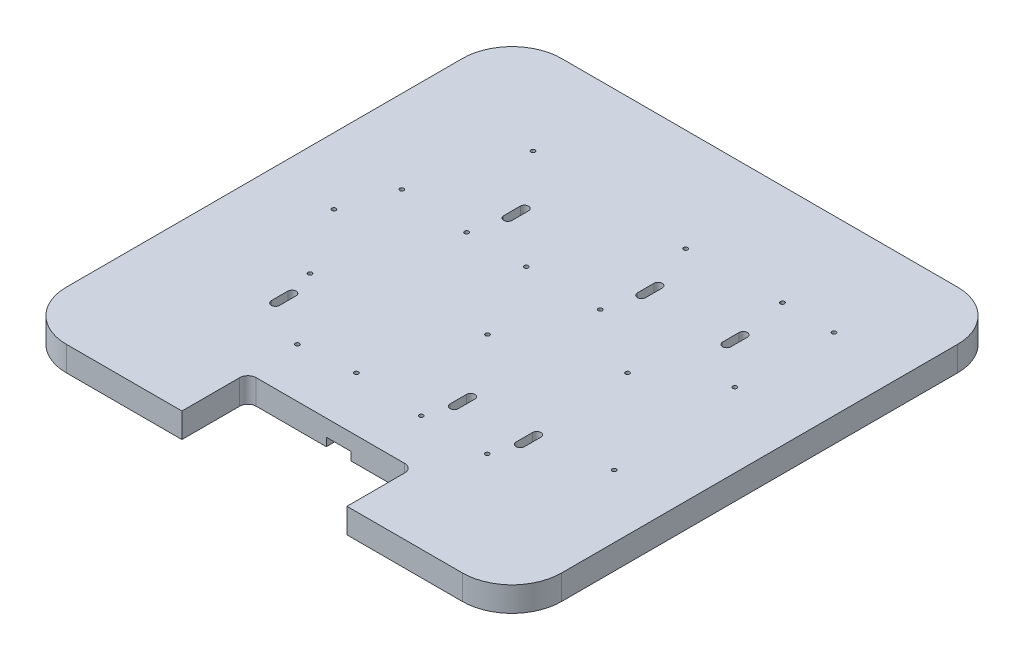
SolidWorks part; units mm, degrees
material "Красное дерево"
ref_plane "Спереди" through (0, 0, 0) normal (0, 0, 1) x (1, 0, 0)
ref_plane "Сверху" through (0, 0, 0) normal (0, 1, 0) x (1, 0, 0)
ref_plane "Справа" through (0, 0, 0) normal (1, 0, 0) x (0, 0, -1)
sketch "Эскиз основания" plane through (0, 0, 0) normal (0, 1, 0) x (1, 0, 0)
  line L0 (-90, -220) -> (90, -220)
  line L1 (-240, 300) -> (240, 300)
  line L2 (-300, 240) -> (-300, -240)
  line L3 (-240, -300) -> (-100, -300)
  line L4 (300, 240) -> (300, -240)
  line L5 (-100, -230) -> (-100, -300)
  line L7 (100, -230) -> (100, -300)
  line L8 (100, -300) -> (240, -300)
  arc A0 (240, -300) -> (300, -240) centre (240, -240) ccw
  arc A1 (240, 300) -> (300, 240) centre (240, 240) cw
  arc A2 (-240, 300) -> (-300, 240) centre (-240, 240) ccw
  arc A3 (-300, -240) -> (-240, -300) centre (-240, -240) ccw
  arc A6 (90, -220) -> (100, -230) centre (90, -230) cw
  arc A7 (-90, -220) -> (-100, -230) centre (-90, -230) ccw
  point P9 (300, 300)
  point P12 (-300, 300)
  point P15 (0, 0)
  dimension "D3" = 60
  dimension "D10" = 10
  dimension "D2" = 600
  dimension "D1" = 600
  dimension "D4" = 300
  dimension "D5" = 300
  dimension "D6" = 200
  dimension "D8" = 100
  dimension "D7" = 80
extrude "Основание" add sketch "Эскиз основания" against normal blind 30
sketch "Эскиз разметки под крепёж" plane through (0, 0, 0) normal (0, 1, 0) x (1, 0, 0)
  line L0 (-372.0217, 60) -> (388.5777, 60) construction
  line L1 (-372.0217, -160) -> (374.4585, -160) construction
  line L2 (0, -364.7935) -> (0, 383.2318) construction
  circle A0 centre (-115, 60) radius 2.5
  circle A1 centre (47, 60) radius 2.5
  circle A2 centre (210, 60) radius 2.5
  circle A3 centre (-100, -160) radius 2.5
  circle A4 centre (50, -160) radius 2.5
  circle A5 centre (130, -160) radius 2.5
  circle A6 centre (-42.72, 60) radius 2.5
  circle A7 centre (-199.29, 65.75) radius 2.5
  circle A8 centre (-160.19, 185.5) radius 2.5
  circle A9 centre (34.8068, 175.55) radius 2.5
  circle A10 centre (150.2162, 177.55) radius 2.5
  circle A11 centre (212.76, 177.55) radius 2.5
  circle A12 centre (-166.6668, -78.149) radius 2.5
  circle A13 centre (-219.52, 3.7) radius 2.5
  circle A14 centre (-34.29, -154.25) radius 2.5
  circle A15 centre (4.81, -34.5) radius 2.5
  circle A16 centre (223.895, -100) radius 2.5
  circle A17 centre (130, 10) radius 2.5
  dimension "D2" = 5
  dimension "D3" = 5
  dimension "D4" = 5
  dimension "D9" = 5
  dimension "D10" = 5
  dimension "D11" = 5
  dimension "D7" = 5
  dimension "D18" = 5
  dimension "D19" = 5
  dimension "D20" = 5
  dimension "D21" = 5
  dimension "D22" = 5
  dimension "D23" = 5
  dimension "D24" = 5
  dimension "D25" = 5
  dimension "D26" = 5
  dimension "D27" = 5
  dimension "D28" = 5
  dimension "D5" = 60
  dimension "D6" = 220
  dimension "D8" = 130
  dimension "D12" = 50
  dimension "D13" = 100
  dimension "D14" = 210
  dimension "D15" = 47
  dimension "D16" = 115
  dimension "D17" = 89.72
  dimension "D29" = 84.29
  dimension "D30" = 5.75
  dimension "D31" = 125.5
  dimension "D32" = 45.19
  dimension "D33" = 12.1932
  dimension "D34" = 115.55
  dimension "D35" = 2.76
  dimension "D36" = 117.55
  dimension "D37" = 59.7838
  dimension "D38" = 84.29
  dimension "D39" = 5.75
  dimension "D40" = 125.5
  dimension "D41" = 45.19
  dimension "D42" = 81.851
  dimension "D43" = 66.6668
  dimension "D44" = 163.7
  dimension "D45" = 119.52
  dimension "D46" = 170
  dimension "D47" = 93.895
  dimension "D48" = 60
extrude "Разметка под крепёж" cut sketch "Эскиз разметки под крепёж" against normal through all
sketch "Эскиз проерзей для проводов" plane through (0, 0, 0) normal (0, 1, 0) x (1, 0, 0)
  line L0 (-105, 120) -> (-105, 100) construction
  line L1 (-100, 120) -> (-100, 100)
  line L2 (-110, 120) -> (-110, 100)
  line L3 (57, 120) -> (57, 100) construction
  line L4 (62, 120) -> (62, 100)
  line L5 (52, 120) -> (52, 100)
  line L6 (160.2162, 120) -> (160.2162, 100) construction
  line L7 (165.2162, 120) -> (165.2162, 100)
  line L8 (155.2162, 120) -> (155.2162, 100)
  line L9 (-156.6668, -110) -> (-156.6668, -130) construction
  line L10 (-151.6668, -110) -> (-151.6668, -130)
  line L11 (-161.6668, -110) -> (-161.6668, -130)
  line L12 (60, -110) -> (60, -130) construction
  line L13 (65, -110) -> (65, -130)
  line L14 (55, -110) -> (55, -130)
  line L15 (140, -110) -> (140, -130) construction
  line L16 (145, -110) -> (145, -130)
  line L17 (135, -110) -> (135, -130)
  arc A0 (-100, 120) -> (-110, 120) centre (-105, 120) ccw
  arc A1 (-110, 100) -> (-100, 100) centre (-105, 100) ccw
  circle A2 centre (150.2162, 177.55) radius 2.5 construction
  circle A3 centre (-115, 60) radius 2.5 construction
  arc A4 (62, 120) -> (52, 120) centre (57, 120) ccw
  arc A5 (52, 100) -> (62, 100) centre (57, 100) ccw
  circle A6 centre (47, 60) radius 2.5 construction
  arc A7 (165.2162, 120) -> (155.2162, 120) centre (160.2162, 120) ccw
  arc A8 (155.2162, 100) -> (165.2162, 100) centre (160.2162, 100) ccw
  arc A10 (-151.6668, -110) -> (-161.6668, -110) centre (-156.6668, -110) ccw
  arc A11 (-161.6668, -130) -> (-151.6668, -130) centre (-156.6668, -130) ccw
  arc A12 (65, -110) -> (55, -110) centre (60, -110) ccw
  arc A13 (55, -130) -> (65, -130) centre (60, -130) ccw
  arc A14 (145, -110) -> (135, -110) centre (140, -110) ccw
  arc A15 (135, -130) -> (145, -130) centre (140, -130) ccw
  circle A16 centre (-166.6668, -78.149) radius 2.5 construction
  circle A17 centre (50, -160) radius 2.5 construction
  circle A18 centre (130, -160) radius 2.5 construction
  point P2 (-105, 110)
  point P12 (57, 110)
  point P21 (160.2162, 110)
  point P28 (-156.6668, -120)
  point P35 (60, -120)
  point P42 (140, -120)
  dimension "D1" = 5
  dimension "D2" = 100
  dimension "D4" = 5
  dimension "D6" = 5
  dimension "D7" = 5
  dimension "D9" = 5
  dimension "D5" = 5
  dimension "D11" = 5
  dimension "D12" = 5
  dimension "D13" = 5
  dimension "D17" = 5
  dimension "D18" = 5
  dimension "D19" = 5
  dimension "D3" = 20
  dimension "D8" = 20
  dimension "D10" = 20
  dimension "D14" = 20
  dimension "D15" = 20
  dimension "D16" = 20
  dimension "D20" = 110
extrude "Прорезь для проводов" cut sketch "Эскиз проерзей для проводов" against normal through all
ref_plane "Плоскость кабель-канала" through (0, -30, 0) normal (0, 1, 0) x (1, 0, 0)
sketch "Эскиз кабель-канала" plane through (0, -30, 0) normal (0, 1, 0) x (1, 0, 0)
  line L0 (-110, 120) -> (-110, 100) construction
  line L1 (-105, 95) -> (70, 95)
  line L2 (-110, 100) -> (-110, 120)
  line L3 (-105, 125) -> (160.2162, 125)
  line L4 (165.2162, 100) -> (165.2162, 120)
  line L5 (165.2162, 100) -> (165.2162, 120) construction
  line L6 (145, -130) -> (145, -110) construction
  line L7 (-156.6668, -105) -> (70, -105)
  line L8 (-161.6668, -110) -> (-161.6668, -130)
  line L9 (-156.6668, -135) -> (-10, -135)
  line L10 (145, -110) -> (145, -130)
  line L11 (-161.6668, -110) -> (-161.6668, -130) construction
  line L12 (-90, -220) -> (90, -220) construction
  line L14 (75, 90) -> (75, -100)
  line L16 (105, 90) -> (105, -100)
  line L18 (-5, -140) -> (-5, -220)
  line L19 (-5, -220) -> (25, -220)
  line L20 (25, -140) -> (25, -220)
  line L21 (110, 95) -> (160.2162, 95)
  line L22 (110, -105) -> (140, -105)
  line L23 (30, -135) -> (140, -135)
  arc A0 (160.2162, 125) -> (165.2162, 120) centre (160.2162, 120) cw
  arc A1 (160.2162, 95) -> (165.2162, 100) centre (160.2162, 100) ccw
  arc A2 (-105, 95) -> (-110, 100) centre (-105, 100) cw
  arc A3 (-110, 120) -> (-105, 125) centre (-105, 120) cw
  arc A4 (140, -105) -> (145, -110) centre (140, -110) cw
  arc A5 (140, -135) -> (145, -130) centre (140, -130) ccw
  arc A6 (-161.6668, -130) -> (-156.6668, -135) centre (-156.6668, -130) ccw
  arc A7 (-156.6668, -105) -> (-161.6668, -110) centre (-156.6668, -110) ccw
  arc A8 (-10, -135) -> (-5, -140) centre (-10, -140) cw
  arc A9 (30, -135) -> (25, -140) centre (30, -140) ccw
  arc A10 (75, -100) -> (70, -105) centre (70, -100) cw
  arc A11 (110, -105) -> (105, -100) centre (110, -100) cw
  arc A12 (110, 95) -> (105, 90) centre (110, 90) ccw
  arc A13 (70, 95) -> (75, 90) centre (70, 90) cw
  point P15 (-110, 95)
  point P18 (-110, 125)
  point P29 (145, -105)
  point P32 (145, -135)
  point P57 (105, -105)
  dimension "D3" = 5
  dimension "D6" = 5
  dimension "D11" = 5
  dimension "D1" = 30
  dimension "D2" = 95
  dimension "D4" = 30
  dimension "D5" = 105
  dimension "D7" = 30
  dimension "D8" = 30
  dimension "D9" = 5
  dimension "D10" = 75
extrude "Каебель-канал" cut sketch "Эскиз кабель-канала" along normal blind 10
equation "\"box_width\"= 200мм"
equation "\"box_height\"= 80мм"
equation "\"D6@Эскиз основания\"=\"box_width\""
equation "\"D8@Эскиз основания\"=\"box_width\"/2"
equation "\"D7@Эскиз основания\"=\"box_height\""
equation "\"drill\"= 5мм"
equation "\"D2@Эскиз разметки под крепёж\" = \"drill\""
equation "\"D3@Эскиз разметки под крепёж\" = \"drill\""
equation "\"D4@Эскиз разметки под крепёж\" = \"drill\""
equation "\"D9@Эскиз разметки под крепёж\" = \"drill\""
equation "\"D10@Эскиз разметки под крепёж\" = \"drill\""
equation "\"D11@Эскиз разметки под крепёж\" = \"drill\""
equation "\"D7@Эскиз разметки под крепёж\"=\"drill\""
equation "\"D18@Эскиз разметки под крепёж\"=\"drill\""
equation "\"D19@Эскиз разметки под крепёж\"=\"drill\""
equation "\"D20@Эскиз разметки под крепёж\"=\"drill\""
equation "\"D21@Эскиз разметки под крепёж\"=\"drill\""
equation "\"D22@Эскиз разметки под крепёж\"=\"drill\""
equation "\"D23@Эскиз разметки под крепёж\"=\"drill\""
equation "\"D24@Эскиз разметки под крепёж\"=\"drill\""
equation "\"D25@Эскиз разметки под крепёж\"=\"drill\""
equation "\"D26@Эскиз разметки под крепёж\"=\"drill\""
equation "\"D27@Эскиз разметки под крепёж\"=\"drill\""
equation "\"D28@Эскиз разметки под крепёж\"=\"drill\""
equation "\"D1@Основание\"=\"width\""
